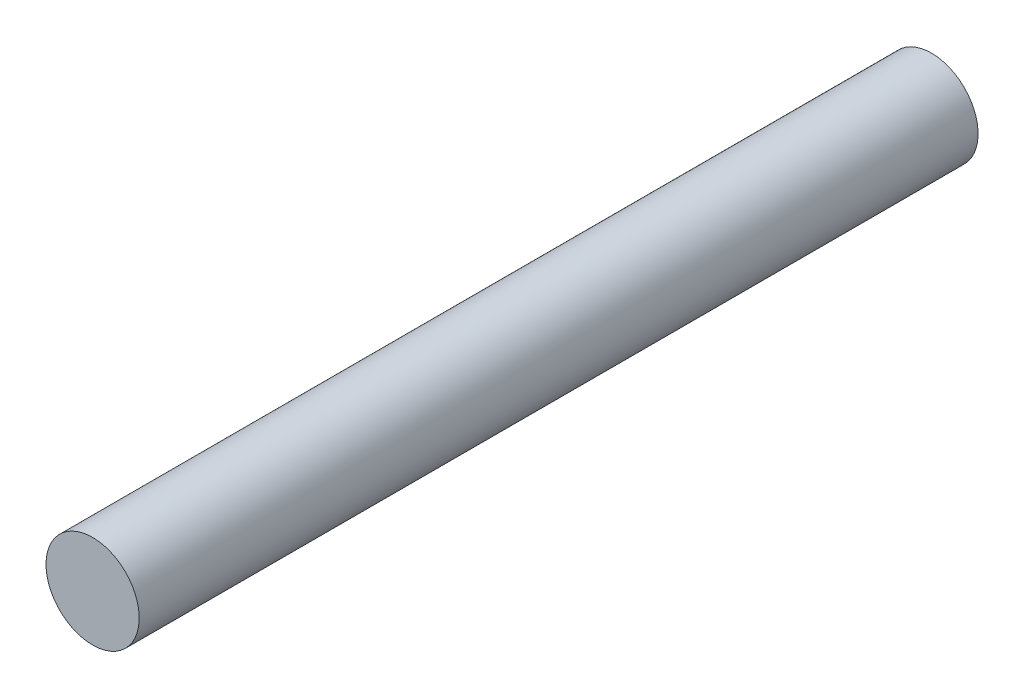
SolidWorks part; units mm, degrees
ref_plane "Front Plane" through (0, 0, 0) normal (0, 0, 1) x (1, 0, 0)
ref_plane "Top Plane" through (0, 0, 0) normal (0, 1, 0) x (1, 0, 0)
ref_plane "Right Plane" through (0, 0, 0) normal (1, 0, 0) x (0, 0, -1)
sketch "Sketch1" plane through (0, 0, 0) normal (0, 0, 1) x (1, 0, 0)
  circle A0 centre (0, 0) radius 10
extrude "Boss-Extrude1" add sketch "Sketch1" along normal blind 180
